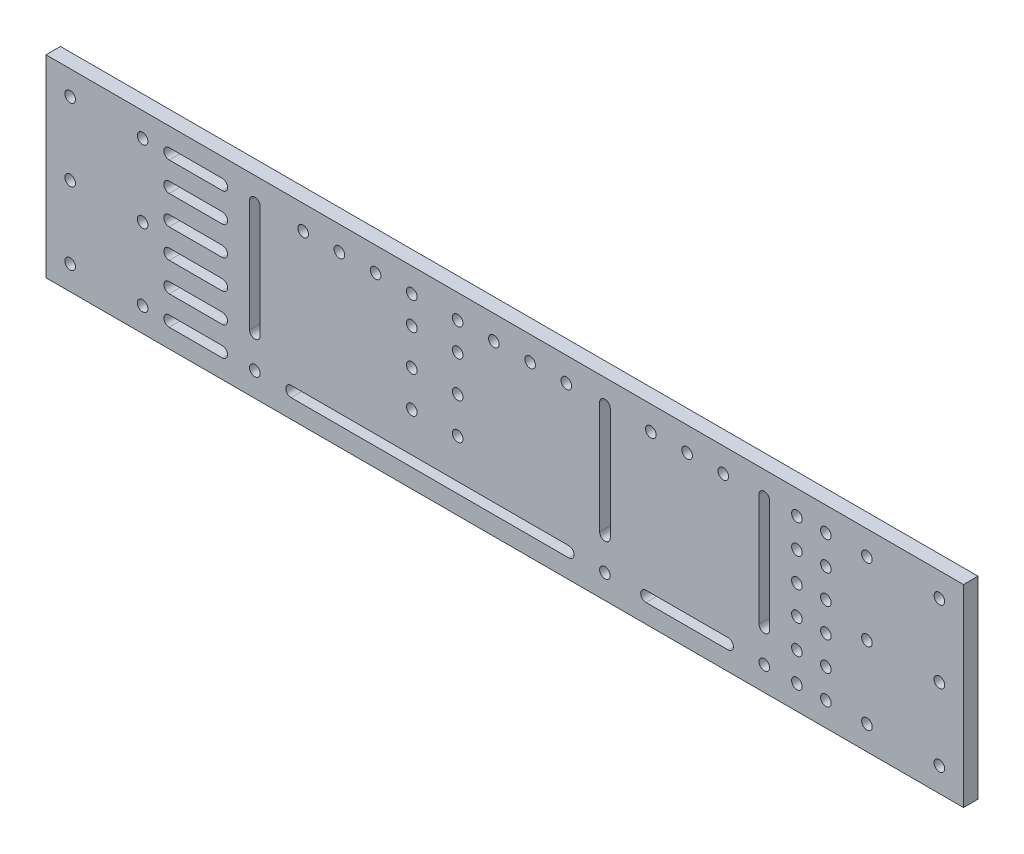
SolidWorks part; units mm, degrees
ref_plane "Front Plane" through (0, 0, 0) normal (0, 0, 1) x (1, 0, 0)
ref_plane "Top Plane" through (0, 0, 0) normal (0, 1, 0) x (1, 0, 0)
ref_plane "Right Plane" through (0, 0, 0) normal (1, 0, 0) x (0, 0, -1)
ref_plane "Plane1" through (0, 0, -15.5) normal (0, 0, -1) x (-1, 0, 0)
sketch "Sketch1" plane through (0, 0, -15.5) normal (0, 0, -1) x (-1, 0, 0)
  line L0 (280, 15.8) -> (258, 15.8)
  line L1 (258, 20.2) -> (280, 20.2)
  line L2 (280, -8.2) -> (258, -8.2)
  line L3 (258, -3.8) -> (280, -3.8)
  line L4 (280, -32.2) -> (258, -32.2)
  line L5 (258, -27.8) -> (280, -27.8)
  line L6 (-49, -40) -> (331, -40)
  line L7 (331, -40) -> (331, 40)
  line L8 (331, 40) -> (-49, 40)
  line L9 (-49, 40) -> (-49, -40)
  line L10 (280, -20.2) -> (258, -20.2)
  line L11 (258, -15.8) -> (280, -15.8)
  line L12 (280, 3.8) -> (258, 3.8)
  line L13 (258, 8.2) -> (280, 8.2)
  line L14 (280, 27.8) -> (258, 27.8)
  line L15 (258, 32.2) -> (280, 32.2)
  line L16 (31.3, -16.5) -> (31.3, 30)
  line L17 (35.7, 30) -> (35.7, -16.5)
  line L18 (48.5, -27.8) -> (82.5, -27.8)
  line L19 (82.5, -32.2) -> (48.5, -32.2)
  line L20 (97.3, -16.5) -> (97.3, 30)
  line L21 (101.7, 30) -> (101.7, -16.5)
  line L22 (242.3, -16.5) -> (242.3, 30)
  line L23 (246.7, 30) -> (246.7, -16.5)
  line L24 (229.5, -32.2) -> (114.5, -32.2)
  line L25 (114.5, -27.8) -> (229.5, -27.8)
  circle A0 centre (-9, -30) radius 2.2
  circle A1 centre (-9, 30) radius 2.2
  circle A2 centre (-9, 0) radius 2.2
  circle A3 centre (-39, -30) radius 2.2
  circle A4 centre (-39, 30) radius 2.2
  circle A5 centre (-39, 0) radius 2.2
  circle A6 centre (291, 30) radius 2.2
  circle A7 centre (321, -30) radius 2.2
  circle A8 centre (321, 0) radius 2.2
  circle A9 centre (33.5, -30) radius 2.2
  circle A10 centre (65.5, 30) radius 2.2
  circle A11 centre (99.5, -30) radius 2.2
  circle A12 centre (115.5, 30) radius 2.2
  circle A13 centre (160.5, -11.5) radius 2.2
  circle A14 centre (160.5, 18.5) radius 2.2
  circle A15 centre (179.5, -11.5) radius 2.2
  circle A16 centre (179.5, 18.5) radius 2.2
  circle A17 centre (194.5, 30) radius 2.2
  circle A18 centre (224.5, 30) radius 2.2
  arc A19 (280, 20.2) -> (280, 15.8) centre (280, 18) cw
  arc A20 (258, 15.8) -> (258, 20.2) centre (258, 18) cw
  arc A21 (280, -3.8) -> (280, -8.2) centre (280, -6) cw
  arc A22 (258, -8.2) -> (258, -3.8) centre (258, -6) cw
  arc A23 (280, -27.8) -> (280, -32.2) centre (280, -30) cw
  arc A24 (258, -32.2) -> (258, -27.8) centre (258, -30) cw
  circle A25 centre (8, 6) radius 2.2
  circle A26 centre (20, -30) radius 2.2
  circle A27 centre (8, -18) radius 2.2
  circle A28 centre (20, 18) radius 2.2
  circle A29 centre (8, 30) radius 2.2
  circle A30 centre (20, -6) radius 2.2
  circle A31 centre (8, -6) radius 2.2
  circle A32 centre (20, 6) radius 2.2
  circle A33 centre (8, 18) radius 2.2
  circle A34 centre (20, 30) radius 2.2
  circle A35 centre (8, -30) radius 2.2
  circle A36 centre (20, -18) radius 2.2
  arc A37 (280, -15.8) -> (280, -20.2) centre (280, -18) cw
  arc A38 (258, -20.2) -> (258, -15.8) centre (258, -18) cw
  arc A39 (280, 8.2) -> (280, 3.8) centre (280, 6) cw
  arc A40 (258, 3.8) -> (258, 8.2) centre (258, 6) cw
  arc A41 (280, 32.2) -> (280, 27.8) centre (280, 30) cw
  arc A42 (258, 27.8) -> (258, 32.2) centre (258, 30) cw
  circle A43 centre (244.5, -30) radius 2.2
  circle A44 centre (209.5, 30) radius 2.2
  circle A45 centre (179.5, 30) radius 2.2
  circle A46 centre (179.5, 3.5) radius 2.2
  circle A47 centre (160.5, 30) radius 2.2
  circle A48 centre (160.5, 3.5) radius 2.2
  circle A49 centre (130.5, 30) radius 2.2
  circle A50 centre (145.5, 30) radius 2.2
  circle A51 centre (80.5, 30) radius 2.2
  circle A52 centre (50.5, 30) radius 2.2
  arc A53 (31.3, 30) -> (35.7, 30) centre (33.5, 30) cw
  arc A54 (35.7, -16.5) -> (31.3, -16.5) centre (33.5, -16.5) cw
  arc A55 (82.5, -27.8) -> (82.5, -32.2) centre (82.5, -30) cw
  arc A56 (48.5, -32.2) -> (48.5, -27.8) centre (48.5, -30) cw
  arc A57 (97.3, 30) -> (101.7, 30) centre (99.5, 30) cw
  arc A58 (101.7, -16.5) -> (97.3, -16.5) centre (99.5, -16.5) cw
  arc A59 (242.3, 30) -> (246.7, 30) centre (244.5, 30) cw
  arc A60 (246.7, -16.5) -> (242.3, -16.5) centre (244.5, -16.5) cw
  arc A61 (229.5, -27.8) -> (229.5, -32.2) centre (229.5, -30) cw
  arc A62 (114.5, -32.2) -> (114.5, -27.8) centre (114.5, -30) cw
  circle A63 centre (321, 30) radius 2.2
  circle A64 centre (291, 0) radius 2.2
  circle A65 centre (291, -30) radius 2.2
extrude "Boss-Extrude1" add sketch "Sketch1" against normal blind 6
